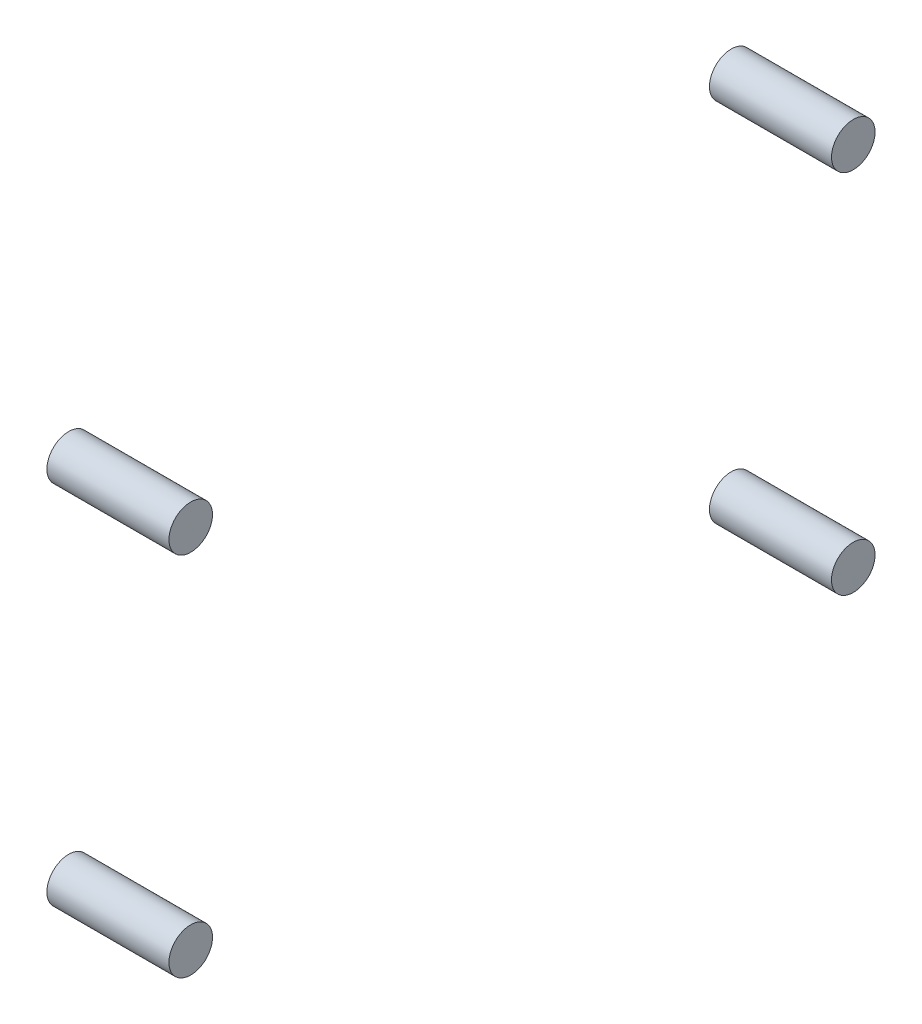
SolidWorks part; units mm, degrees
ref_plane "Front Plane" through (0, 0, 0) normal (0, 0, 1) x (1, 0, 0)
ref_plane "Top Plane" through (0, 0, 0) normal (0, 1, 0) x (1, 0, 0)
ref_plane "Right Plane" through (0, 0, 0) normal (1, 0, 0) x (0, 0, -1)
sketch "Sketch2" plane through (0, 0, 0) normal (1, 0, 0) x (0, 0, -1)
  circle A0 centre (75.89, 6.4263) radius 1.25
  circle A1 centre (37.89, 6.4263) radius 1.25
  circle A2 centre (37.89, -14.5737) radius 1.25
  circle A3 centre (75.89, -14.5737) radius 1.25
  dimension "D1" = 2.5
extrude "Boss-Extrude1" add sketch "Sketch2" against normal blind 7
hole_wizard "#45 (0.082) Diameter Hole1" positions "3DSketch2" profile "Sketch4" hole size "#45" standard "ANSI Inch"
sketch3d "3DSketch2"
  line L0 (-7, -14.5737, -37.89) -> (0, -14.5737, -37.89) construction
  line L1 (-7, -14.5737, -75.89) -> (0, -14.5737, -75.89) construction
  line L2 (-7, 6.4263, -75.89) -> (0, 6.4263, -75.89) construction
  line L3 (-7, 6.4263, -37.89) -> (0, 6.4263, -37.89) construction
  point P0 (-7, -14.5737, -37.89)
  point P4 (-7, -14.5737, -75.89)
  point P8 (-7, 6.4263, -75.89)
  point P12 (-7, 6.4263, -37.89)
sketch "Sketch4" plane through (-7, -14.5737, -37.89) normal (0, 1, 0) x (0, 0, 1)
  line L0 (0, 0) -> (0, 6)
  line L1 (0, 6) -> (1.0414, 5.3743)
  line L2 (1.0414, 5.3743) -> (1.0414, 0)
  line L5 (1.0414, 0) -> (0, 0)
  line L10 (0, 6) -> (-1.0414, 5.3743) construction
  line L11 (0, -6.35) -> (0, 107.95) construction
  dimension "Hole Dia." = 2.0828
  dimension "Hole Depth" = 6
  dimension "Drill Angle" = 118
